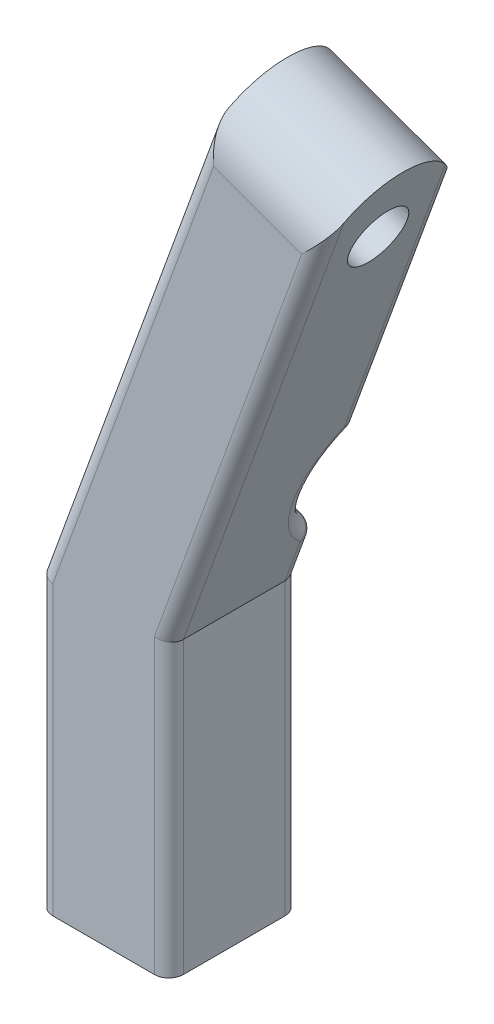
SolidWorks part; units mm, degrees
ref_plane "Ön Düzlem" through (0, 0, 0) normal (0, 0, 1) x (1, 0, 0)
ref_plane "Üst Düzlem" through (0, 0, 0) normal (0, 1, 0) x (1, 0, 0)
ref_plane "Sağ Düzlem" through (0, 0, 0) normal (1, 0, 0) x (0, 0, -1)
sketch "Çizim1" plane through (0, 0, 0) normal (0, 0, 1) x (1, 0, 0)
  line L0 (0, 0) -> (0, 20)
  line L1 (0, 20) -> (12.6815, 54.8421)
  line L2 (12.6815, 54.8421) -> (20.6287, 51.9495)
  line L3 (20.6287, 51.9495) -> (9, 20)
  line L4 (9, 20) -> (9, 0)
  line L5 (9, 0) -> (0, 0)
  line L6 (0, 20) -> (0, 44.3587) construction
  dimension "D1" = 20
  dimension "D2" = 20
  dimension "D3" = 9
  dimension "D4" = 34
  dimension "D5" = 20
extrude "Yükseklik-Ekstrüzyon1" add sketch "Çizim1" along normal blind 9
sketch "Çizim2" plane through (0, 0, 0) normal (0, -1, 0) x (1, 0, 0)
  line L0 (0, 0) -> (9, 0) construction
  line L1 (9, 9) -> (9, 0) construction
  circle A0 centre (4.5, 4.5) radius 2.5
  dimension "D1" = 5
  dimension "D2" = 4.5
  dimension "D3" = 4.5
extrude "Kes-Ekstrüzyon1" cut sketch "Çizim2" against normal blind 15
sketch "Çizim3" plane through (1.5193, -0.553, 0) normal (0.9397, -0.342, 0) x (0, 0, -1)
  line L0 (3, 19.4585) -> (3, 52.1521) construction
  line L1 (0, 21.872) -> (0, 55.872) construction
  circle A0 centre (3, 29.372) radius 5
  dimension "D3" = 10
  dimension "D1" = 3
  dimension "D2" = 7.5
extrude "Kes-Ekstrüzyon2" cut sketch "Çizim3" against normal blind 15
fillet "Radyus1" radius 1 2 edges at (8.9596, 32.2527, 0) (6.2235, 24.7352, 0)
fillet "Radyus3" radius 1 12 edges at (16.8617, 41.5998, 0) (12.9551, 30.8665, 0.0871) (11.5652, 27.0477, 2) (10.1752, 23.2289, 0.0871) (8.9145, 44.4924, 0) (5.0079, 33.759, 0.0871) (3.618, 29.9402, 2) (2.228, 26.1214, 0.0871) (9.5178, 21.4226, 0) (1.0442, 22.8689, 0) (9, 10, 0) (0, 10, 0)
fillet "Radyus4" radius 1 4 edges at (9, 10, 9) (14.8143, 35.9748, 9) (6.3407, 37.421, 9) (0, 10, 9)
sketch "Çizim4" plane through (1.5193, -0.553, 0) normal (0.9397, -0.342, 0) x (0, 0, -1)
  line L0 (-4.5, 55.872) -> (-4.5, 40.7151) construction
  line L4 (-9, 55.872) -> (-9, 18.9702) construction
  line L5 (0, 55.872) -> (0, 33.8442) construction
  line L6 (-8, 55.872) -> (-1, 55.872) construction
  line L7 (-9, 51.372) -> (-9, 55.872)
  line L8 (-9, 55.872) -> (0, 55.872)
  line L9 (0, 55.872) -> (0, 51.372)
  line L11 (-9, 51.372) -> (-9.0328, 51.2712)
  arc A0 (0, 51.372) -> (-9, 51.372) centre (-4.5, 51.372) ccw
  line M4 (-1, 55.872) -> (-8, 55.872)
  line M5 (-8, 55.872) -> (-8, 21.872)
  line M9 (-1, 33.8442) -> (-1, 55.872)
extrude "Kes-Ekstrüzyon3" cut sketch "Çizim4" against normal blind 15 contours A0 L8 L7 M5 | A0 L8 M5 | A0 M9 M4 | A0 L9 L8 M9
sketch "Çizim5" plane through (-6.4279, 2.3396, 0) normal (-0.9397, 0.342, 0) x (0, 0, 1)
  line L0 (4.5, 55.872) -> (4.5, 34.6611) construction
  line L1 (1, 54.2005) -> (1, 33.8442) construction
  line L2 (8, 18.7939) -> (8, 54.2005) construction
  circle A0 centre (4.5, 50.872) radius 2
  arc A1 (8, 54.2005) -> (1, 54.2005) centre (4.5, 51.372) ccw construction
  dimension "D2" = 4
  dimension "D1" = 5
extrude "Kes-Ekstrüzyon4" cut sketch "Çizim5" against normal blind 15
